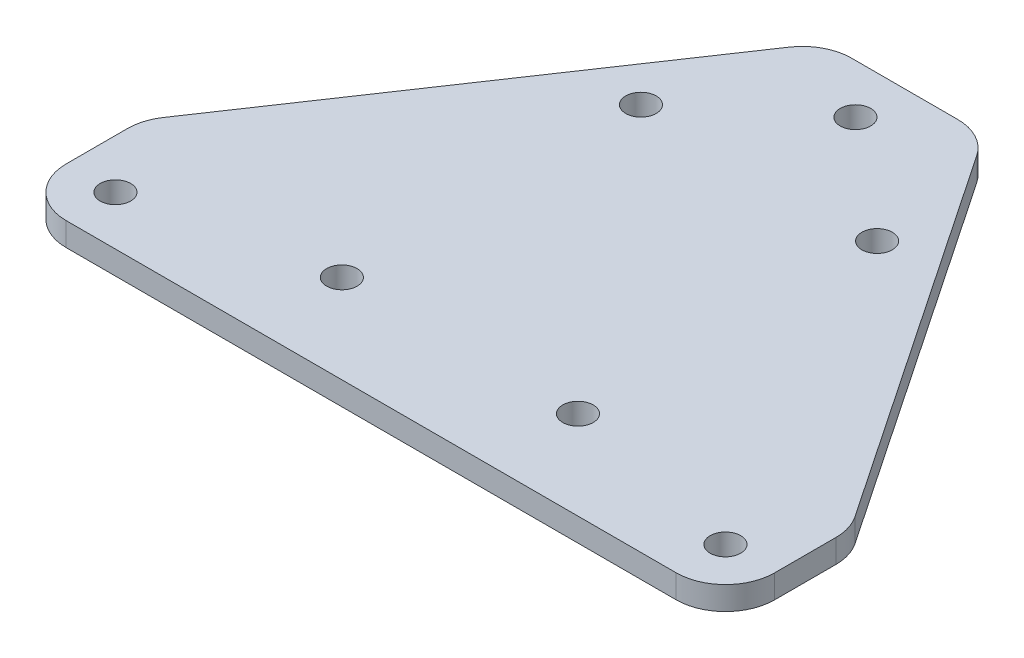
SolidWorks part; units mm, degrees
ref_plane "Front Plane" through (0, 0, 0) normal (0, 0, 1) x (1, 0, 0)
ref_plane "Top Plane" through (0, 0, 0) normal (0, 1, 0) x (1, 0, 0)
ref_plane "Right Plane" through (0, 0, 0) normal (1, 0, 0) x (0, 0, -1)
sketch "Sketch1" plane through (0, 0, 0) normal (0, 1, 0) x (1, 0, 0)
  line L0 (-41.9629, 0) -> (43.8937, 0) construction
  line L1 (-5.3946, 30) -> (5.3946, 30)
  line L2 (-36, -12.9889) -> (-36, -19.2154)
  line L3 (-31, -24.2154) -> (31, -24.2154)
  line L4 (36, -12.9889) -> (36, -19.2154)
  line L5 (0, 28.6403) -> (0, -39.4528) construction
  line L6 (-9.5407, 27.7946) -> (-35.1461, -10.1944)
  line L7 (9.5407, 27.7946) -> (35.1461, -10.1944)
  circle A0 centre (0, 25) radius 1.55
  circle A1 centre (-31, -19.2154) radius 1.55
  circle A2 centre (31, -19.2154) radius 1.55
  circle A3 centre (12, -15.2) radius 1.55
  circle A4 centre (-12, -15.2) radius 1.55
  circle A5 centre (-12, 15.2) radius 1.55
  circle A6 centre (12, 15.2) radius 1.55
  arc A7 (-36, -19.2154) -> (-31, -24.2154) centre (-31, -19.2154) ccw
  arc A8 (36, -19.2154) -> (31, -24.2154) centre (31, -19.2154) cw
  arc A9 (36, -12.9889) -> (35.1461, -10.1944) centre (31, -12.9889) ccw
  arc A10 (-36, -12.9889) -> (-35.1461, -10.1944) centre (-31, -12.9889) cw
  arc A11 (9.5407, 27.7946) -> (5.3946, 30) centre (5.3946, 25) ccw
  arc A12 (-5.3946, 30) -> (-9.5407, 27.7946) centre (-5.3946, 25) ccw
  point P31 (36, -11.4612)
  point P34 (-36, -11.4612)
  point P37 (8.0542, 30)
  point P40 (-8.0542, 30)
  dimension "D1" = 3.1
  dimension "D2" = 24
  dimension "D3" = 30.4
  dimension "D4" = 54
  dimension "D14" = 5
  dimension "D19" = 5
  dimension "D5" = 62
  dimension "D6" = 54
  dimension "D7" = 12
  dimension "D8" = 15.2
  dimension "D9" = 25
  dimension "D10" = 5
  dimension "D11" = 5
  dimension "D12" = 5
  dimension "D13" = 5
  dimension "D15" = 5
  dimension "D16" = 5
  dimension "D17" = 50
  dimension "D18" = 50
extrude "Boss-Extrude1" add sketch "Sketch1" along normal blind 2.38
